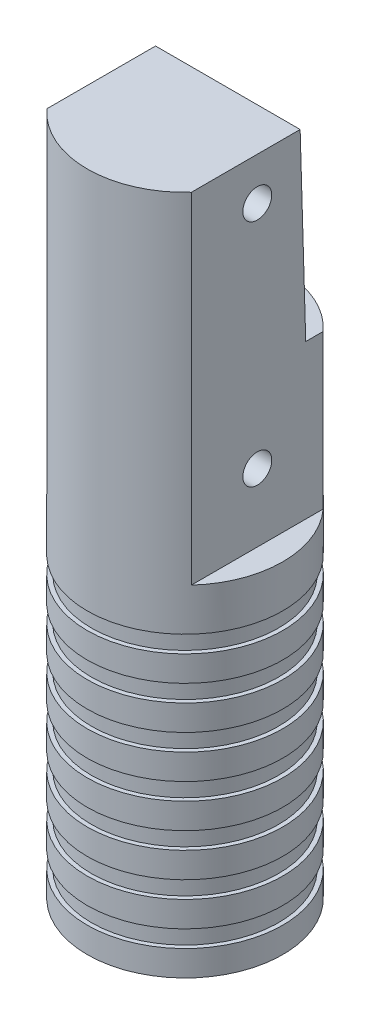
SolidWorks part; units mm, degrees
material "6061-T6 (SS)"
ref_plane "Front Plane" through (0, 0, 0) normal (0, 0, 1) x (1, 0, 0)
ref_plane "Top Plane" through (0, 0, 0) normal (0, 1, 0) x (1, 0, 0)
ref_plane "Right Plane" through (0, 0, 0) normal (1, 0, 0) x (0, 0, -1)
sketch "Sketch2" plane through (0, 0, 0) normal (0, 0, 1) x (1, 0, 0)
  line L0 (-11.5, 0) -> (11.5, 0)
  line L1 (11.5, 0) -> (11.5, -40)
  line L2 (11.5, -40) -> (0, -40)
  line L4 (0, 0) -> (0, -40)
  line L6 (-11.5, -40) -> (0, -40)
  line L7 (-11.5, 0) -> (-11.5, -40)
  point P4 (0, 0)
  dimension "D1" = 23
  dimension "D4" = 40
revolve "Revolve1" add sketch "Sketch2" angle 360 about L4
sketch "Sketch3" plane through (0, 0, 0) normal (0, 0, 1) x (1, 0, 0)
  line L0 (-11.5, -40) -> (11.5, -40) construction
  line L1 (-11.5, -40) -> (11.5, -40)
  line L2 (11.5, -40) -> (11.5, -37)
  line L3 (11.5, -40) -> (11.5, 0) construction
  line L4 (11.5, -37) -> (11, -37)
  line L5 (11, -37) -> (11, -35)
  line L6 (11, -35) -> (11.5, -35)
  line L7 (11.5, -37) -> (11.5, -35)
  dimension "D1" = 2
  dimension "D2" = 0.5
  dimension "D3" = 3
revolve "Cut-Revolve1" cut sketch "Sketch3" angle 360 about L4
pattern_linear "LPattern1" count 7 spacing 5 along (0, 1, 0) of "Cut-Revolve1"
sketch "Sketch4" plane through (0, -40, 0) normal (0, -1, 0) x (1, 0, 0)
  point P0 (0, 0)
sketch "Sketch6" plane through (0, 0, 0) normal (0, 1, 0) x (1, 0, 0)
  line L0 (-8.5, 7.746) -> (-8.5, -7.746)
  line L2 (0, 0) -> (0, 11.5) construction
  line L3 (8.5, 7.746) -> (8.5, -7.746)
  line L4 (0, 0) -> (-8.5, 0) construction
  line L5 (-8.5, 1.5) -> (0, 1.5) construction
  arc A0 (8.5, 7.746) -> (-8.5, 7.746) centre (0, 0) ccw
  circle A1 centre (0, 0) radius 11.5 construction
  arc A2 (8.5, -7.746) -> (-8.5, -7.746) centre (0, 0) cw
  point P7 (-11.5, 0)
  dimension "D1" = 3
  dimension "D2" = 1.5
extrude "Boss-Extrude1" add sketch "Sketch6" along normal blind 40
hole_wizard "Ø15.0 (15) Diameter Hole1" positions "Sketch4" profile "Sketch5" hole size "Ø15.0" standard "ANSI Metric"
sketch "Sketch5" plane through (0, -40, 0) normal (1, 0, 0) x (0, 0, -1)
  line L0 (0, 0) -> (0, 44.5065)
  line L1 (0, 44.5065) -> (7.5, 40)
  line L2 (7.5, 40) -> (7.5, 0)
  line L5 (7.5, 0) -> (0, 0)
  line L10 (0, 44.5065) -> (-7.5, 40) construction
  line L11 (0, -6.35) -> (0, 107.95) construction
  dimension "Hole Dia." = 15
  dimension "Hole Depth" = 40
  dimension "Drill Angle" = 118
sketch "Sketch8" plane through (8.5, 0, 0) normal (1, 0, 0) x (0, 0, -1)
  line L2 (0, 8) -> (0, 35) construction
  line L3 (7.746, 0) -> (-7.746, 0) construction
  circle A0 centre (0, 8) radius 1.5 construction
  point P0 (0, 8)
  point P1 (0, 35)
  dimension "D1" = 3
  dimension "D2" = 8
  dimension "D3" = 27
hole_wizard "M3 Clearance Hole1" positions "Sketch8" profile "Sketch14" hole size "M3" standard "ANSI Metric" end condition through all
sketch "Sketch14" plane through (8.5, 8, 0) normal (0, 1, 0) x (0, 0, -1)
  line L0 (0, 0) -> (0, 20)
  line L1 (0, 20) -> (1.7, 20)
  line L2 (1.7, 20) -> (1.7, 0)
  line L5 (1.7, 0) -> (0, 0)
  line L11 (0, -6.35) -> (0, 107.95) construction
  dimension "Thru Hole Dia." = 3.4
  dimension "Thru Hole Depth" = 20
sketch "Sketch16" plane through (0, 0, 0) normal (1, 0, 0) x (0, 0, -1)
  line L0 (50.0175, 86.3497) -> (50.0175, 73.3497) construction
  line L1 (50.0175, -3.6503) -> (50.0175, 9.3497) construction
  line L2 (5.0377, 40) -> (5.6954, 18.0816)
  line L3 (5.6954, 18.0816) -> (11.5, 18.0816)
  line L4 (11.5, 40) -> (7.746, 40) construction
  line L5 (11.5, 40) -> (7.746, 40)
  line L6 (7.746, 40) -> (5.0377, 40)
  line L7 (11.5, -5) -> (11.5, 40) construction
  line L8 (11.5, 18.0816) -> (11.5, 40)
  circle A0 centre (0, 8) radius 1.7 construction
  circle A1 centre (0, 35) radius 1.7 construction
  circle A2 centre (0, 8) radius 1.7
  circle A3 centre (0, 35) radius 1.7
  arc A4 (50.0175, -3.6503) -> (50.0175, 86.3497) centre (50.0175, 41.3497) cw construction
  arc A5 (50.0175, 73.3497) -> (50.0175, 9.3497) centre (50.0175, 41.3497) ccw construction
  dimension "D1" = 32
  dimension "D4" = 13
  dimension "D2" = 60.1162
  dimension "D3" = 50.4189
extrude "Cut-Extrude1" cut sketch "Sketch16" against normal through all both and the other way through all
